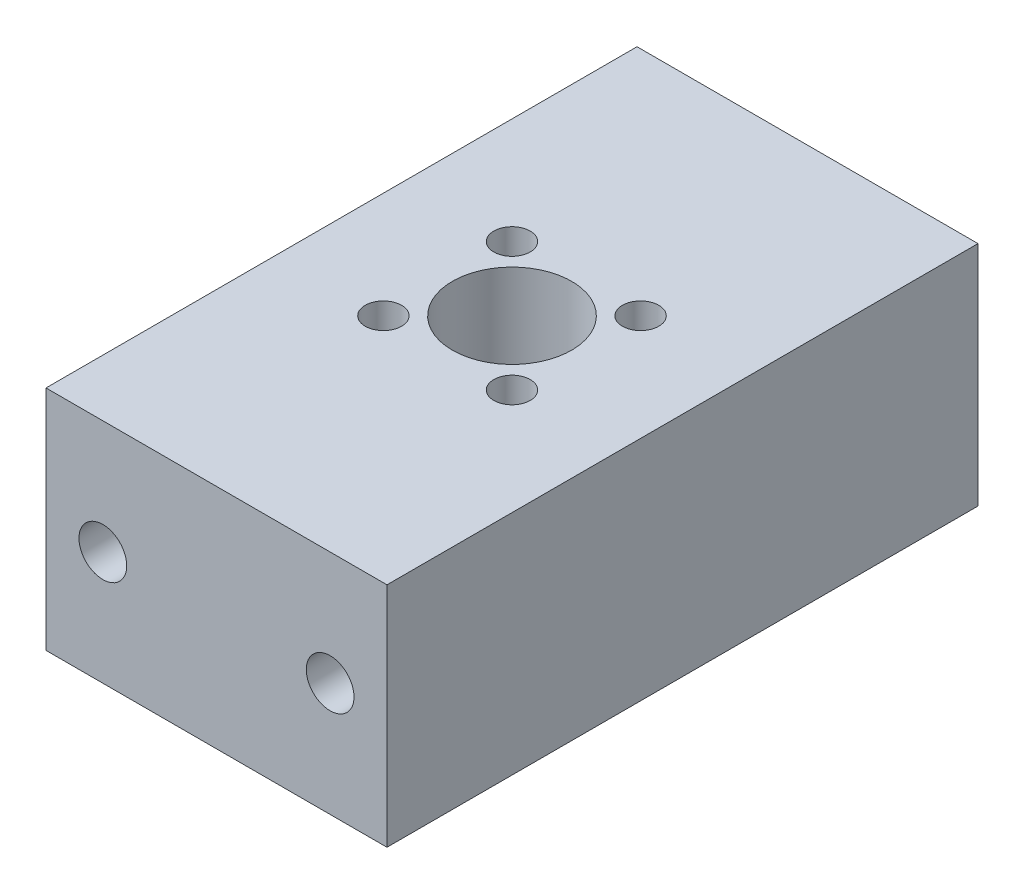
SolidWorks part; units mm, degrees
ref_plane "前视基准面" through (0, 0, 0) normal (0, 0, 1) x (1, 0, 0)
ref_plane "上视基准面" through (0, 0, 0) normal (0, 1, 0) x (1, 0, 0)
ref_plane "右视基准面" through (0, 0, 0) normal (1, 0, 0) x (0, 0, -1)
sketch "草图1" plane through (0, 0, 0) normal (0, 0, 1) x (1, 0, 0)
  line L1 (0, 0) -> (30, 0)
  line L2 (0, 0) -> (0, 20)
  line L3 (0, 20) -> (30, 20)
  line L4 (30, 0) -> (30, 20)
  circle A0 centre (5, 10) radius 2.1
  circle A2 centre (25, 10) radius 2.1
  point P7 (0, 0)
  point P13 (0, 0)
  point P14 (0, 0)
  point P15 (0, 0)
  point P16 (0, 0)
  dimension "D7" = 4.2
  dimension "D1" = 30
  dimension "D2" = 20
  dimension "D3" = 5
  dimension "D4" = 10
  dimension "D5" = 5
extrude "凸台-拉伸1" add sketch "草图1" along normal blind 52
sketch "草图2" plane through (0, 20, 0) normal (0, 1, 0) x (1, 0, 0)
  line L2 (0, -52) -> (0, 0) construction
  line L3 (9.3431, -31.6569) -> (20.6569, -31.6569) construction
  line L4 (9.3431, -31.6569) -> (9.3431, -20.3431) construction
  line L5 (9.3431, -20.3431) -> (20.6569, -20.3431) construction
  line L6 (20.6569, -31.6569) -> (20.6569, -20.3431) construction
  line L7 (9.3431, -31.6569) -> (20.6569, -20.3431) construction
  line L8 (9.3431, -20.3431) -> (20.6569, -31.6569) construction
  circle A0 centre (15, -26) radius 5.25
  circle A7 centre (9.3431, -31.6569) radius 1.6
  circle A8 centre (9.3431, -20.3431) radius 1.6
  circle A9 centre (20.6569, -20.3431) radius 1.6
  circle A10 centre (20.6569, -31.6569) radius 1.6
  point P6 (26.0747, -20.3431)
  point P7 (26.0747, -31.6569)
  point P10 (0, 0)
  point P11 (10.3504, -27.0043)
  point P14 (0, -26)
  dimension "D1" = 10.5
  dimension "D3" = 3.2
  dimension "D2" = 16
  dimension "D4" = 15
extrude "切除-拉伸1" cut sketch "草图2" against normal through all
